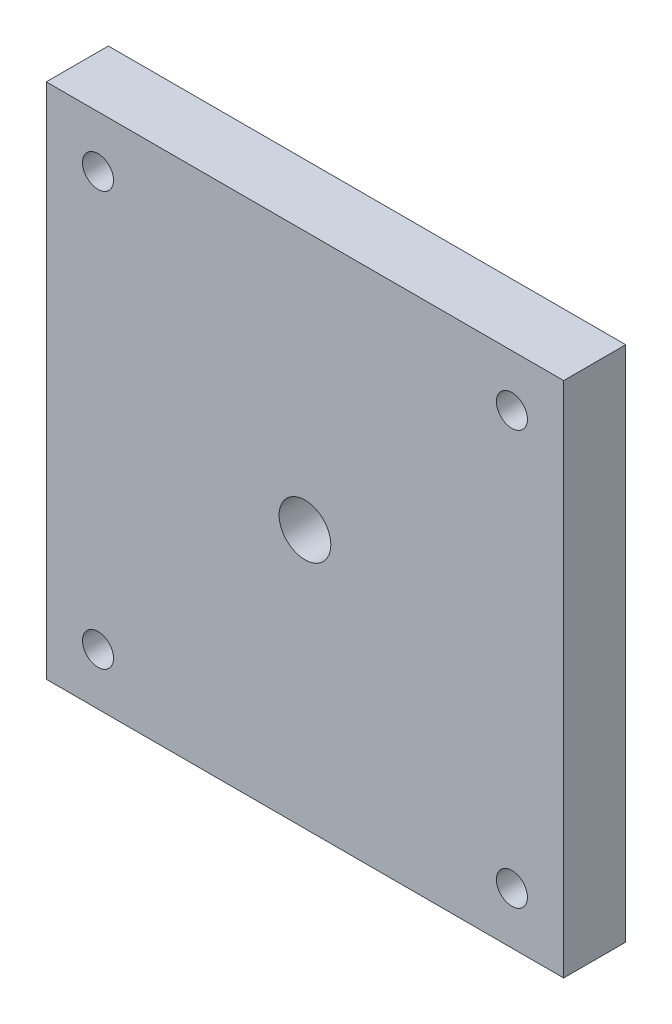
SolidWorks part; units mm, degrees
ref_plane "前视基准面" through (0, 0, 0) normal (0, 0, 1) x (1, 0, 0)
ref_plane "上视基准面" through (0, 0, 0) normal (0, 1, 0) x (1, 0, 0)
ref_plane "右视基准面" through (0, 0, 0) normal (1, 0, 0) x (0, 0, -1)
sketch "草图1" plane through (0, 0, 0) normal (0, 0, 1) x (1, 0, 0)
  line L0 (0, 24.2958) -> (0, -18.2642) construction
  line L1 (-25, 25) -> (25, 25)
  line L2 (-25, 25) -> (-25, -25)
  line L3 (-25, -25) -> (25, -25)
  line L4 (25, 25) -> (25, -25)
  line L5 (-32.2198, 0) -> (32.714, 0) construction
  circle A0 centre (0, 0) radius 2.5
  circle A1 centre (-20, 20) radius 1.5
  circle A2 centre (20, 20) radius 1.5
  circle A3 centre (20, -20) radius 1.5
  circle A4 centre (-20, -20) radius 1.5
  dimension "D1" = 5
  dimension "D6" = 3
  dimension "D8" = 20
  dimension "D2" = 50
  dimension "D3" = 50
  dimension "D4" = 25
  dimension "D5" = 25
  dimension "D7" = 20
extrude "凸台-拉伸1" add sketch "草图1" along normal blind 6
